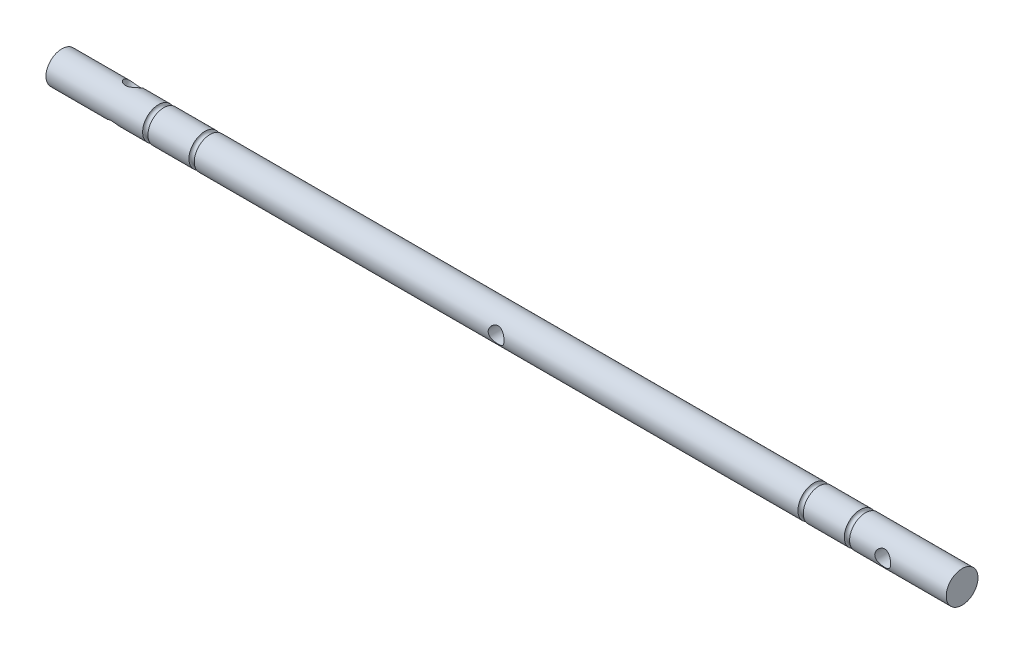
SolidWorks part; units mm, degrees
ref_plane "Front Plane" through (0, 0, 0) normal (1, 0, 0) x (0, 1, 0)
ref_plane "Top Plane" through (0, 0, 0) normal (0, 0, 1) x (0, 1, 0)
ref_plane "Right Plane" through (0, 0, 0) normal (0, 1, 0) x (-1, 0, 0)
sketch "Sketch1" plane through (0, 0, 0) normal (1, 0, 0) x (0, 1, 0)
  circle A0 centre (0, 0) radius 3
  dimension "D1" = 6
extrude "Boss-Extrude1" add sketch "Sketch1" along normal blind 170
sketch "Sketch2" plane through (0, 0, 0) normal (0, 0, 1) x (0, 1, 0)
  line L0 (-3, -170) -> (3, -170) construction
  circle A0 centre (0, -158) radius 1.5
  circle A1 centre (0, -85) radius 1.5
  dimension "D1" = 3
  dimension "D3" = 3
  dimension "D2" = 12
  dimension "D4" = 85
extrude "Cut-Extrude1" cut sketch "Sketch2" against normal through all both and the other way through all
ref_plane "Plane1" through (0, 0, 0) normal (0, 0.866, -0.5) x (-1, 0, 0)
sketch "Sketch3" plane through (0, 0, 0) normal (0, 0.866, -0.5) x (-1, 0, 0)
  line L0 (-170, 0) -> (0, 0) construction
  line L1 (0, -3) -> (0, 3) construction
  circle A0 centre (-12, 0) radius 1.5
  dimension "D1" = 3
  dimension "D2" = 12
extrude "Cut-Extrude2" cut sketch "Sketch3" against normal through all both and the other way through all
ref_plane "Plane2" through (151.25, 0, 0) normal (1, 0, 0) x (0, 1, 0)
sketch "Sketch4" plane through (151.25, 0, 0) normal (1, 0, 0) x (0, 1, 0)
  circle A0 centre (0, 0) radius 3 construction
  circle A1 centre (0, 0) radius 3
sweep "Cut-Sweep1" cut path "Sketch4" circular profile diameter 1 parameters "D3"=1
pattern_linear "LPattern1" count 2 spacing 8.75 along (-1, 0, 0) of "Cut-Sweep1"
ref_plane "Plane3" through (85, 0, 0) normal (1, 0, 0) x (0, 1, 0)
mirror "Mirror1" about plane through (85, 0, 0) normal (1, 0, 0) of "LPattern1", "Cut-Sweep1"
